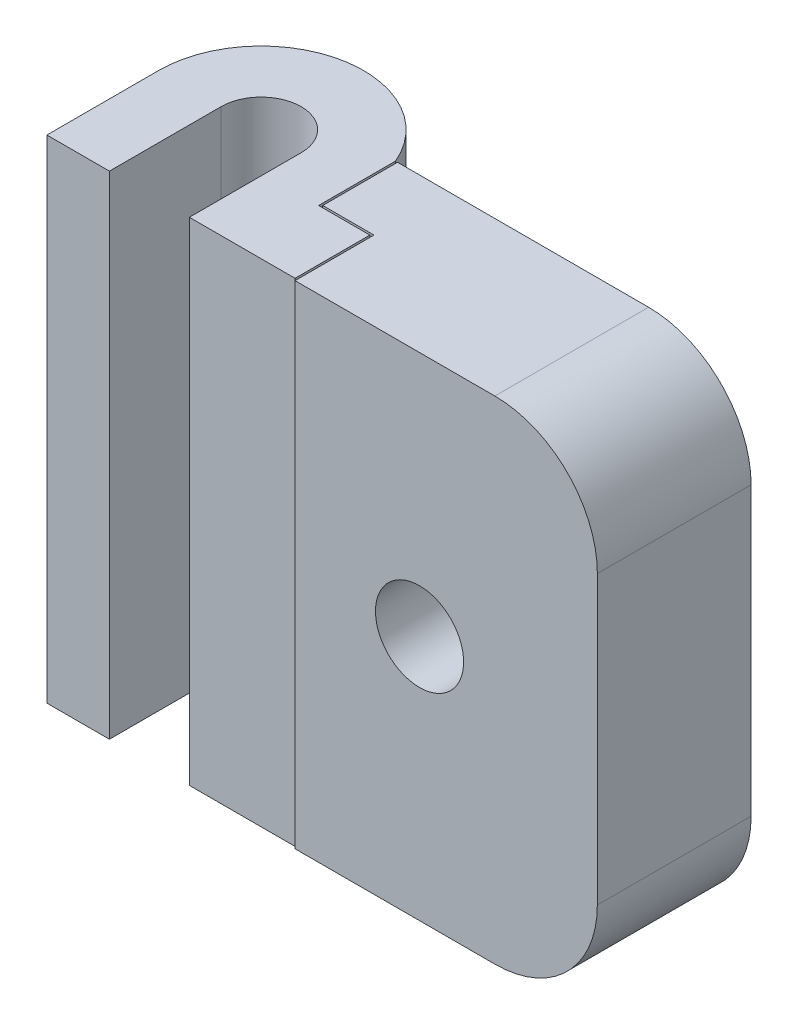
SolidWorks part; units mm, degrees
ref_plane "Front Plane" through (0, 0, 0) normal (0, 0, 1) x (1, 0, 0)
ref_plane "Top Plane" through (0, 0, 0) normal (0, 1, 0) x (1, 0, 0)
ref_plane "Right Plane" through (0, 0, 0) normal (1, 0, 0) x (0, 0, -1)
sketch "Sketch4" plane through (0, 0, 0) normal (0, 1, 0) x (1, 0, 0)
  line L1 (21.95, 0) -> (21.95, 1.95)
  line L2 (21.95, 1.95) -> (4.6041, 1.95)
  line L3 (1.95, 0) -> (1.95, -5.55)
  line L4 (1.95, -5.55) -> (21.95, -5.55)
  line L5 (21.95, -5.55) -> (21.95, 0)
  line L8 (-5, 0) -> (-5, -5.55)
  line L9 (-5, -5.55) -> (-1.95, -5.55)
  line L10 (-1.95, 0) -> (-1.95, -5.55)
  arc A0 (1.95, 0) -> (-1.95, 0) centre (0, 0) ccw
  arc A1 (4.6041, 1.95) -> (-5, 0) centre (0, 0) ccw
  dimension "D1" = 3.9
  dimension "D2" = 10
  dimension "D3" = 5.55
  dimension "D4" = 20
extrude "Boss-Extrude3" add sketch "Sketch4" along normal blind 24
fillet "Fillet1" radius 5 2 edges at (21.95, 0, 1.8) (21.95, 24, 1.8)
sketch "Sketch10" plane through (0, 0, -1.95) normal (0, 0, -1) x (-1, 0, 0)
  line L0 (-21.95, 19) -> (-21.95, 5) construction
  line L2 (-21.95, 12) -> (-4.6041, 12) construction
  line L3 (-4.6041, 24) -> (-4.6041, 0) construction
  circle A0 centre (-13.277, 12) radius 4.1
  point P4 (-21.95, 12)
  point P5 (-13.277, 12)
  dimension "D1" = 8.2
extrude "Cut-Extrude3" cut sketch "Sketch10" against normal blind 3
sketch "Sketch11" plane through (0, 0, 1.05) normal (0, 0, -1) x (-1, 0, 0)
  circle A0 centre (-13.277, 12) radius 2.15
  circle A1 centre (-13.277, 12) radius 4.1
  circle A2 centre (-13.277, 12) radius 4.1 construction
  dimension "D2" = 4.3
  dimension "D1" = 0
extrude "Cut-Extrude4" cut sketch "Sketch11" against normal through all
sketch "Sketch13" plane through (0, 0, 0) normal (0, -1, 0) x (1, 0, 0)
  line L10 (4.6041, -1.95) -> (4.6041, 1.8)
  line L11 (4.6041, 1.8) -> (7.1041, 1.8)
  line L12 (7.1041, 1.8) -> (7.1041, 5.55)
  line L13 (1.95, 5.55) -> (16.95, 5.55) construction
  line L14 (4.7041, -1.95) -> (4.7041, 1.7)
  line L15 (4.7041, 1.7) -> (7.2041, 1.7)
  line L16 (7.2041, 1.7) -> (7.2041, 5.55)
  line L17 (4.6041, -1.95) -> (4.7041, -1.95)
  line L18 (7.1041, 5.55) -> (7.2041, 5.55)
  dimension "D1" = 2.5
  dimension "D2" = 0.1
extrude "Cut-Extrude5" cut sketch "Sketch13" against normal through all
sketch "Sketch14" plane through (0, 0, 5.55) normal (0, 0, 1) x (1, 0, 0)
  line L4 (1.95, 0) -> (7.1041, 0)
  line L5 (7.1041, 0) -> (7.1041, 24)
  line L6 (7.1041, 24) -> (1.95, 24)
  line L7 (1.95, 24) -> (1.95, 0)
  line L8 (1.95, 0) -> (7.1041, 0)
  line L9 (7.1041, 0) -> (7.1041, 24)
  line L10 (7.1041, 24) -> (1.95, 24)
  line L11 (1.95, 24) -> (1.95, 0)
  line L12 (-5, 0) -> (-1.95, 0)
  line L13 (-1.95, 0) -> (-1.95, 24)
  line L14 (-1.95, 24) -> (-5, 24)
  line L15 (-5, 24) -> (-5, 0)
  line L16 (-5, 0) -> (-1.95, 0)
  line L17 (-1.95, 0) -> (-1.95, 24)
  line L18 (-1.95, 24) -> (-5, 24)
  line L19 (-5, 24) -> (-5, 0)
  dimension "D1" = 0
  dimension "D2" = 0
extrude "Cut-Extrude6" cut sketch "Sketch14" against normal blind 0.1
sketch "Sketch15" plane through (0, 0, 1.05) normal (0, 0, -1) x (-1, 0, 0)
  circle A0 centre (-13.277, 12) radius 2.15 construction
  circle A1 centre (-13.277, 12) radius 2.15
extrude "Boss-Extrude4" add sketch "Sketch15" against normal blind 0.6
